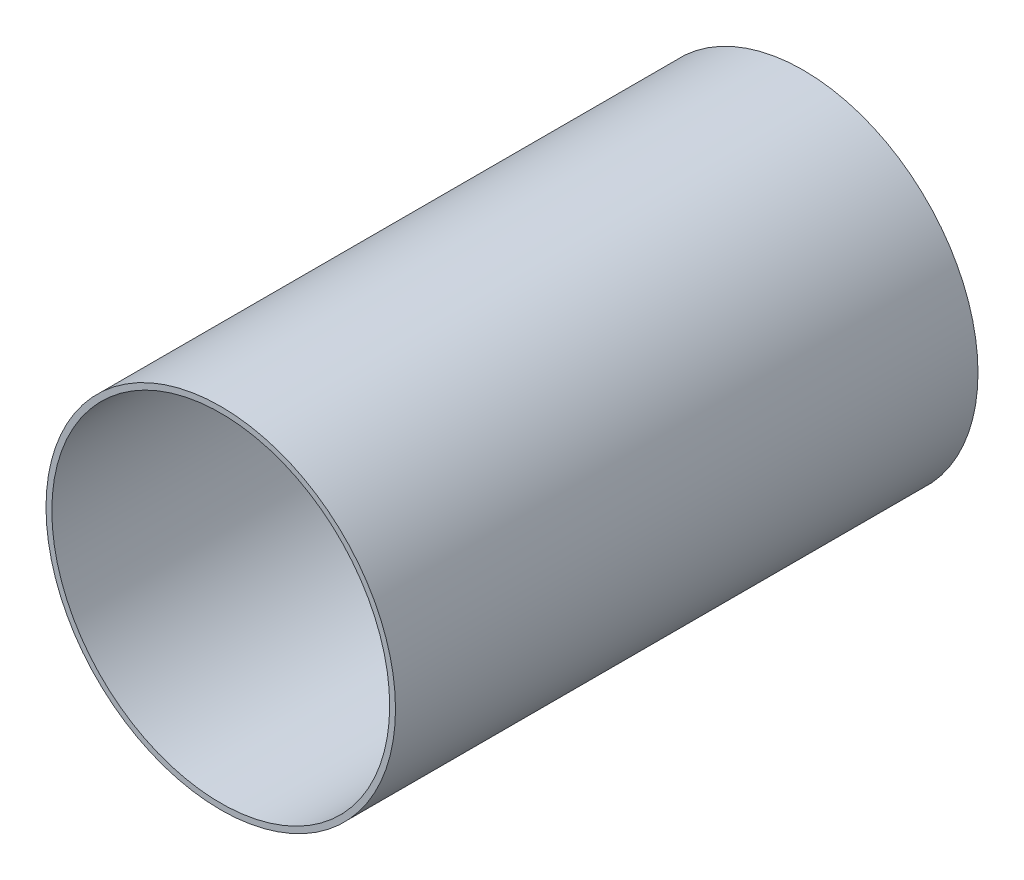
SolidWorks part; units mm, degrees
ref_plane "Front Plane" through (0, 0, 0) normal (0, 0, 1) x (1, 0, 0)
ref_plane "Top Plane" through (0, 0, 0) normal (0, 1, 0) x (1, 0, 0)
ref_plane "Right Plane" through (0, 0, 0) normal (1, 0, 0) x (0, 0, -1)
sketch "Sketch1" plane through (0, 0, 0) normal (0, 0, 1) x (1, 0, 0)
  circle A0 centre (0, 0) radius 30
  circle A1 centre (0, 0) radius 29
  dimension "D1" = 60
  dimension "D2" = 1
extrude "Boss-Extrude1" add sketch "Sketch1" along normal blind 100
